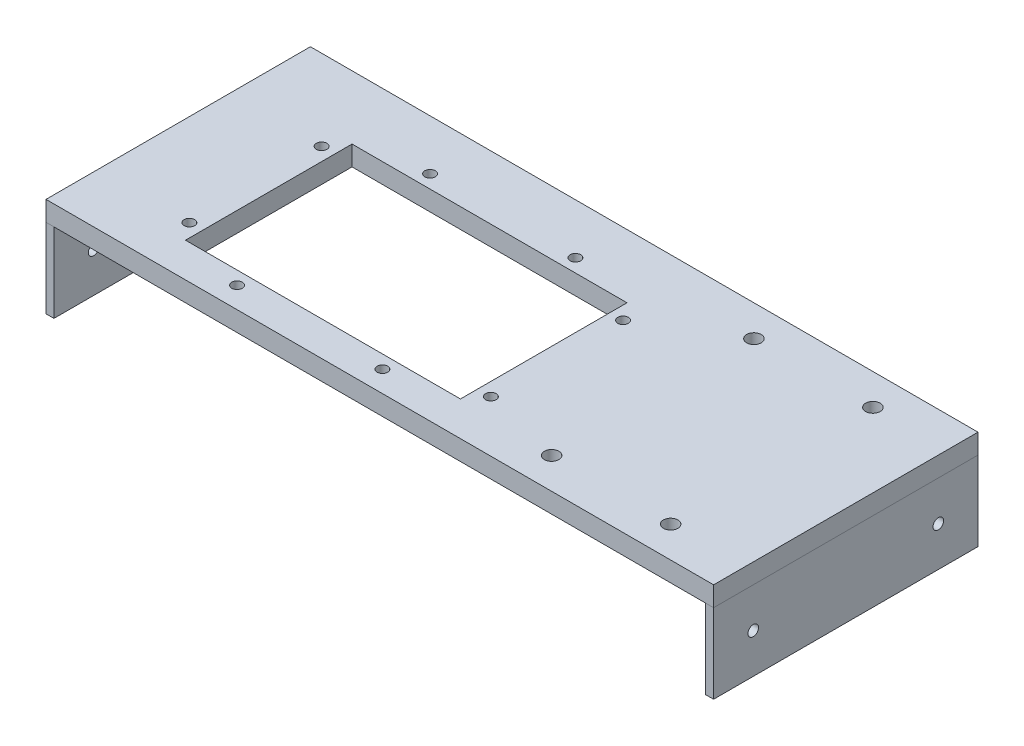
SolidWorks part; units mm, degrees
material "Plain Carbon Steel"
ref_plane "Front Plane" through (0, 0, 0) normal (0, 0, 1) x (1, 0, 0)
ref_plane "Top Plane" through (0, 0, 0) normal (0, 1, 0) x (1, 0, 0)
ref_plane "Right Plane" through (0, 0, 0) normal (1, 0, 0) x (0, 0, -1)
sketch "Sketch1" plane through (0, 0, 0) normal (0, 1, 0) x (1, 0, 0)
  line L0 (0, 0) -> (-252.5, 0) construction
  line L1 (0, 0) -> (0, 100) construction
  line L8 (252.5, 100) -> (-252.5, 100)
  line L9 (-252.5, 100) -> (-252.5, -100)
  line L10 (-252.5, -100) -> (252.5, -100)
  line L11 (252.5, -100) -> (252.5, 100)
  circle A4 centre (227.5, -75) radius 5 construction
  circle A5 centre (227.5, 75) radius 5 construction
  circle A6 centre (-227.5, -75) radius 5 construction
  circle A7 centre (-227.5, 75) radius 5 construction
  circle A16 centre (106.5, -76.5) radius 5.5 construction
  circle A17 centre (196.5, -76.5) radius 5.5 construction
  circle A18 centre (196.5, 76.5) radius 5.5 construction
  circle A19 centre (106.5, 76.5) radius 5.5 construction
  circle A20 centre (106.5, -76.5) radius 5.5
  circle A21 centre (196.5, -76.5) radius 5.5
  circle A22 centre (196.5, 76.5) radius 5.5
  circle A23 centre (106.5, 76.5) radius 5.5
  circle A24 centre (45, -61) radius 4 construction
  circle A25 centre (-14, -84) radius 4 construction
  circle A26 centre (-124, -84) radius 4 construction
  circle A27 centre (-183, -61) radius 4 construction
  circle A28 centre (-183, 39) radius 4 construction
  circle A29 centre (-124, 62) radius 4 construction
  circle A30 centre (45, 39) radius 4 construction
  circle A31 centre (-14, 62) radius 4 construction
  circle A32 centre (45, -61) radius 4
  circle A33 centre (-14, -84) radius 4
  circle A34 centre (-124, -84) radius 4
  circle A35 centre (-183, -61) radius 4
  circle A36 centre (-183, 39) radius 4
  circle A37 centre (-124, 62) radius 4
  circle A38 centre (45, 39) radius 4
  circle A39 centre (-14, 62) radius 4
  dimension "D4" = 25
  dimension "D5" = 10
  dimension "D1" = 505
  dimension "D2" = 200
  dimension "D3" = 25
extrude "Boss-Extrude1" add sketch "Sketch1" against normal blind 15
sketch "Sketch2" plane through (0, -15, 0) normal (0, -1, 0) x (1, 0, 0)
  line L0 (35, -102) -> (35, 94) construction
  line L1 (-173, 74) -> (35, 74)
  line L2 (-173, 74) -> (-173, -52)
  line L3 (-173, -52) -> (35, -52)
  line L4 (35, 74) -> (35, -52)
  line L5 (35, 74) -> (-173, 74) construction
  line L6 (-173, -52) -> (35, -52) construction
  line L7 (-173, 94) -> (-173, -72) construction
extrude "Shredder Opening" cut sketch "Sketch2" against normal through all
sketch "Sketch3" plane through (0, 0, 0) normal (0, 1, 0) x (1, 0, 0)
  line L0 (252.5, 100) -> (-252.5, 100) construction
  line L1 (200, 100) -> (30, 100)
  line L2 (200, 100) -> (200, 176.5)
  line L3 (200, 176.5) -> (30, 176.5)
  line L4 (30, 100) -> (30, 176.5)
  line L8 (115, 176.5) -> (115, 267.7218) construction
  circle A1 centre (175, 151.5) radius 5
  circle A2 centre (55, 151.5) radius 5
extrude "Legs add on" [suppressed] add sketch "Sketch3" against normal through all
sketch "Sketch4" plane through (0, 0, 100) normal (0, 0, 1) x (1, 0, 0)
  line L0 (0, -15) -> (0, -97.7912) construction
  line L1 (-252.5, -15) -> (-246.5, -15)
  line L2 (-252.5, -15) -> (-252.5, -75)
  line L3 (-252.5, -75) -> (-246.5, -75)
  line L4 (-246.5, -15) -> (-246.5, -75)
  line L5 (-252.5, -15) -> (252.5, -15) construction
  line L6 (246.5, -15) -> (246.5, -75)
  line L7 (252.5, -75) -> (246.5, -75)
  line L8 (252.5, -15) -> (252.5, -75)
  line L9 (252.5, -15) -> (246.5, -15)
  dimension "D1" = 60
  dimension "D2" = 6
extrude "Boss-Extrude2" add sketch "Sketch4" against normal through all separate body
sketch "Sketch5" plane through (-252.5, 0, 0) normal (-1, 0, 0) x (0, 0, 1)
  line L0 (0, -75) -> (0, -118.3722) construction
  line L1 (-100, -75) -> (100, -75) construction
  line L2 (100, -15) -> (100, -75) construction
  circle A0 centre (70, -45) radius 4
  circle A1 centre (-70, -45) radius 4
  point P11 (100, -45)
  dimension "D1" = 8
  dimension "D2" = 26
extrude "Cut-Extrude1" cut sketch "Sketch5" against normal through all
